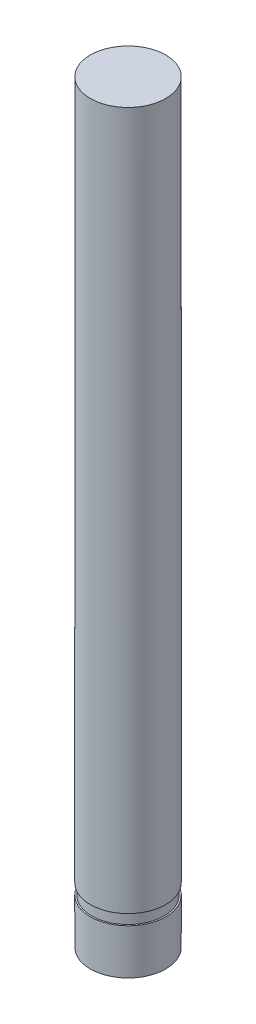
SolidWorks part; units mm, degrees
ref_plane "Front Plane" through (0, 0, 0) normal (0, 0, 1) x (1, 0, 0)
ref_plane "Top Plane" through (0, 0, 0) normal (0, 1, 0) x (1, 0, 0)
ref_plane "Right Plane" through (0, 0, 0) normal (1, 0, 0) x (0, 0, -1)
sketch "Sketch1" plane through (0, 0, 0) normal (0, 1, 0) x (1, 0, 0)
  circle A0 centre (0, 0) radius 2.5
  dimension "D1" = 5
extrude "Boss-Extrude1" add sketch "Sketch1" along normal blind 50
ref_plane "Plane1" through (0, 3, 0) normal (0, -1, 0) x (-1, 0, 0)
sketch "Sketch2" plane through (0, 3, 0) normal (0, -1, 0) x (-1, 0, 0)
  circle A0 centre (0, 0) radius 2.4
  circle A1 centre (0, 0) radius 2.5
  dimension "D1" = 4.8
  dimension "D2" = 5
extrude "Cut-Extrude1" cut sketch "Sketch2" against normal blind 0.7
